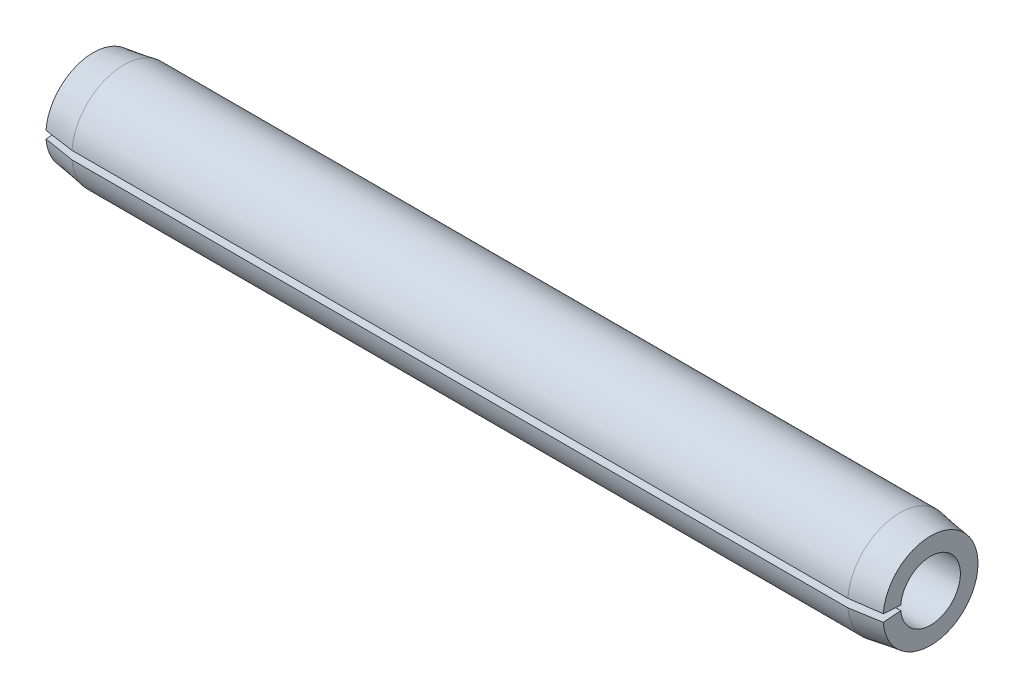
SolidWorks part; units mm, degrees
material "Plain Carbon Steel"
ref_plane "Plane1" through (0, 0, 0) normal (0, 0, 1) x (1, 0, 0)
ref_plane "Plane2" through (0, 0, 0) normal (0, 1, 0) x (1, 0, 0)
ref_plane "Plane3" through (0, 0, 0) normal (1, 0, 0) x (0, 0, -1)
sketch "Sketch1" plane through (0, 0, 0) normal (0, 0, 1) x (1, 0, 0)
  line L0 (-9.525, 0) -> (111.125, 0) construction
  line L1 (0, 1.3589) -> (38.1, 1.3589)
  line L2 (38.1, 1.3589) -> (38.1, 2.159)
  line L3 (38.1, 2.159) -> (36.703, 2.3749)
  line L4 (36.703, 2.3749) -> (1.397, 2.3749)
  line L5 (1.397, 2.3749) -> (0, 2.159)
  line L7 (0, 2.159) -> (0, 1.3589)
  dimension "Diameter" = 4.7498
  dimension "Length" = 38.1
  dimension "Thickness" = 1.016
  dimension "Top_ch_len" = 1.397
  dimension "Bottom_ch_len" = 1.397
  dimension "Bottom_ch_dia" = 4.318
  dimension "Top_ch_dia" = 4.318
revolve "Base-Revolve" add sketch "Sketch1" angle 360 about L0
sketch "Sketch2" plane through (0, 0, 0) normal (-1, 0, 0) x (0, -1, 0)
  line L0 (0, 0) -> (0.1901, 2.4149)
  line L1 (0, -3.175) -> (0, 12.7) construction
  line L2 (0, 0) -> (-0.1901, 2.4149)
  arc A0 (0.1901, 2.4149) -> (-0.1901, 2.4149) centre (0, 0) ccw
  dimension "D1" = 2.4224
  dimension "Gap_ang" = 9
extrude "Gap" cut sketch "Sketch2" against normal through all
equation "\"D1@Sketch2\" = \"Diameter@Sketch1\" * 0.51"
equation "' \"Bottom_ch_dia@Sketch1\" = \"Diameter@Sketch1\" -  ( \"Thickness@Sketch1\" / 2 ) "
equation "' \"Top_ch_dia@Sketch1\" = \"Bottom_ch_dia@Sketch1\""
equation "' \"Top_ch_len@Sketch1\" = \"Bottom_ch_len@Sketch1\""
